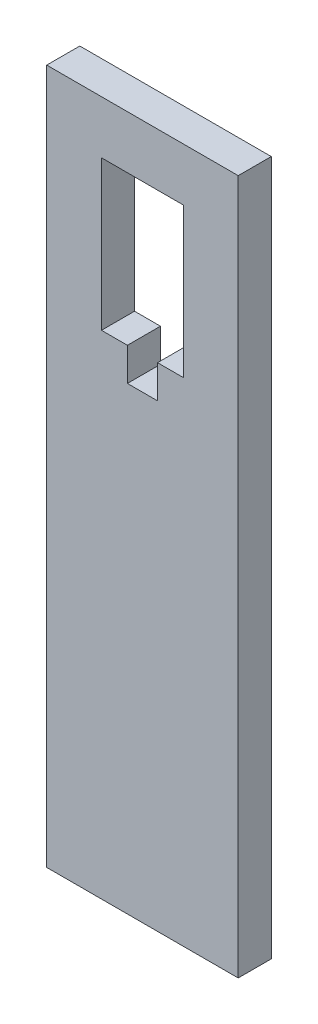
SolidWorks part; units mm, degrees
ref_plane "Front Plane" through (0, 0, 0) normal (0, 0, 1) x (1, 0, 0)
ref_plane "Top Plane" through (0, 0, 0) normal (0, 1, 0) x (1, 0, 0)
ref_plane "Right Plane" through (0, 0, 0) normal (1, 0, 0) x (0, 0, -1)
sketch "Sketch1" plane through (0, 0, 0) normal (0, 0, 1) x (1, 0, 0)
  line L1 (-18.5582, 31.0897) -> (10.4018, 31.0897)
  line L2 (-18.5582, 31.0897) -> (-18.5582, -43.4103)
  line L3 (-18.5582, -43.4103) -> (10.4018, -43.4103)
  line L4 (10.4018, 31.0897) -> (10.4018, -43.4103)
  dimension "D1" = 28.96
  dimension "D2" = 74.5
extrude "Boss-Extrude1" add sketch "Sketch1" along normal blind 5
sketch "Sketch2" plane through (0, 31.0897, 0) normal (0, 1, 0) x (1, 0, 0)
  line L0 (-18.5582, 0) -> (-10.2782, 0)
  line L1 (10.4018, 0) -> (-18.5582, 0) construction
  line L2 (-10.2782, 0) -> (-10.2782, -5)
  line L3 (10.4018, -5) -> (-18.5582, -5) construction
  line L4 (-10.2782, -5) -> (-18.5582, -5)
  line L5 (-18.5582, -5) -> (-18.5582, 0)
  line L6 (10.4018, 0) -> (2.1218, 0)
  line L7 (2.1218, 0) -> (2.1218, -5)
  line L8 (2.1218, -5) -> (10.4018, -5)
  line L9 (10.4018, -5) -> (10.4018, 0)
  dimension "D1" = 12.4
extrude "Boss-Extrude2" add sketch "Sketch2" along normal blind 22.6
sketch "Sketch3" plane through (0, 53.6897, 0) normal (0, 1, 0) x (1, 0, 0)
  line L1 (-18.5582, 0) -> (10.4018, 0)
  line L2 (-18.5582, 0) -> (-18.5582, -5)
  line L3 (-18.5582, -5) -> (10.4018, -5)
  line L4 (10.4018, 0) -> (10.4018, -5)
extrude "Boss-Extrude3" add sketch "Sketch3" along normal blind 8
sketch "Sketch4" plane through (0, 31.0897, 0) normal (0, 1, 0) x (1, 0, 0)
  line L0 (10.4018, 0) -> (-18.5582, 0) construction
  line L1 (-6.3582, 0) -> (-1.7982, 0)
  line L2 (-6.3582, 0) -> (-6.3582, -5)
  line L3 (-6.3582, -5) -> (-1.7982, -5)
  line L4 (-1.7982, 0) -> (-1.7982, -5)
  line L5 (-18.5582, -5) -> (10.4018, -5) construction
  line L6 (-18.5582, 0) -> (-18.5582, -5) construction
  line L7 (10.4018, -5) -> (10.4018, 0) construction
  dimension "D1" = 12.2
  dimension "D2" = 12.2
extrude "Cut-Extrude1" cut sketch "Sketch4" against normal blind 5
